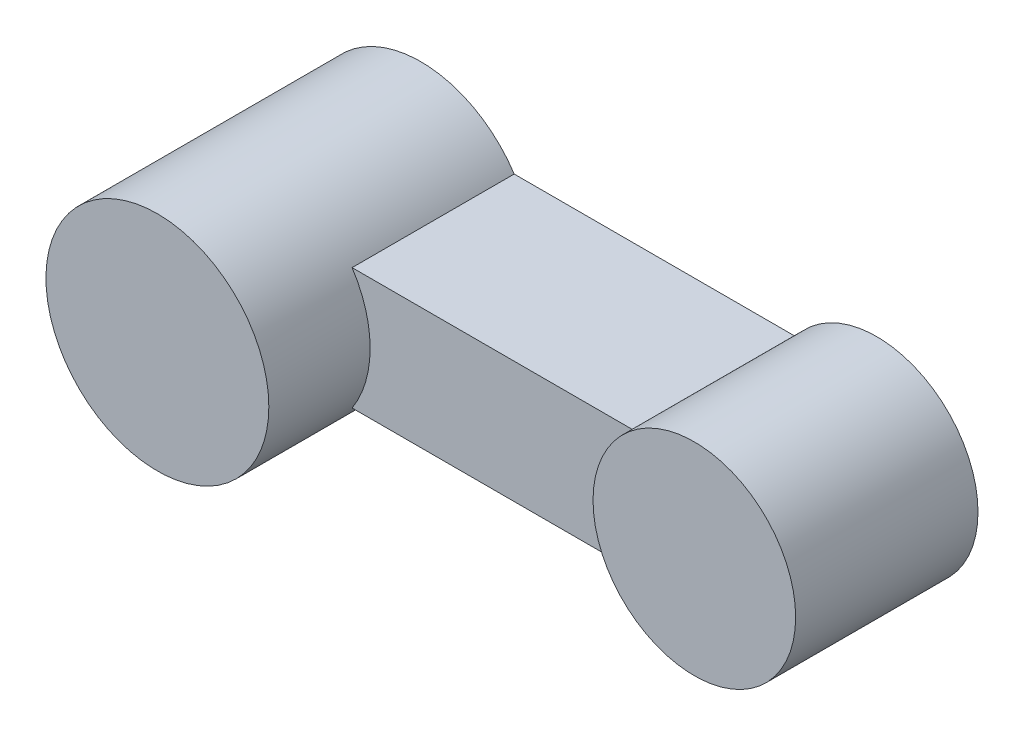
SolidWorks part; units mm, degrees
ref_plane "Front Plane" through (0, 0, 0) normal (0, 0, 1) x (1, 0, 0)
ref_plane "Top Plane" through (0, 0, 0) normal (0, 1, 0) x (1, 0, 0)
ref_plane "Right Plane" through (0, 0, 0) normal (1, 0, 0) x (0, 0, -1)
sketch "草图3" plane through (0, 0, 0) normal (0, 0, 1) x (1, 0, 0)
  line L0 (20, 6) -> (65, 6)
  line L1 (65, 6) -> (65, 18)
  line L2 (65, 18) -> (20, 18)
  line L3 (20, 18) -> (20, 6)
  dimension "x0" = 20
  dimension "x1" = 65
  dimension "y0" = 6
  dimension "y2" = 18
extrude "Bar" add sketch "草图3" along normal blind 16
sketch "草图4" plane through (0, 0, 0) normal (0, 0, 1) x (1, 0, 0)
  circle A0 centre (20, 12) radius 11
  dimension "diameter" = 22
  dimension "x" = 20
  dimension "y" = 12
extrude "RootHub" add sketch "草图4" along normal blind 26
sketch "草图5" plane through (0, 0, 0) normal (0, 0, 1) x (1, 0, 0)
  circle A0 centre (65, 12) radius 10
  dimension "diameter" = 20
  dimension "x" = 65
  dimension "y" = 12
extrude "EndHub" add sketch "草图5" along normal blind 18
